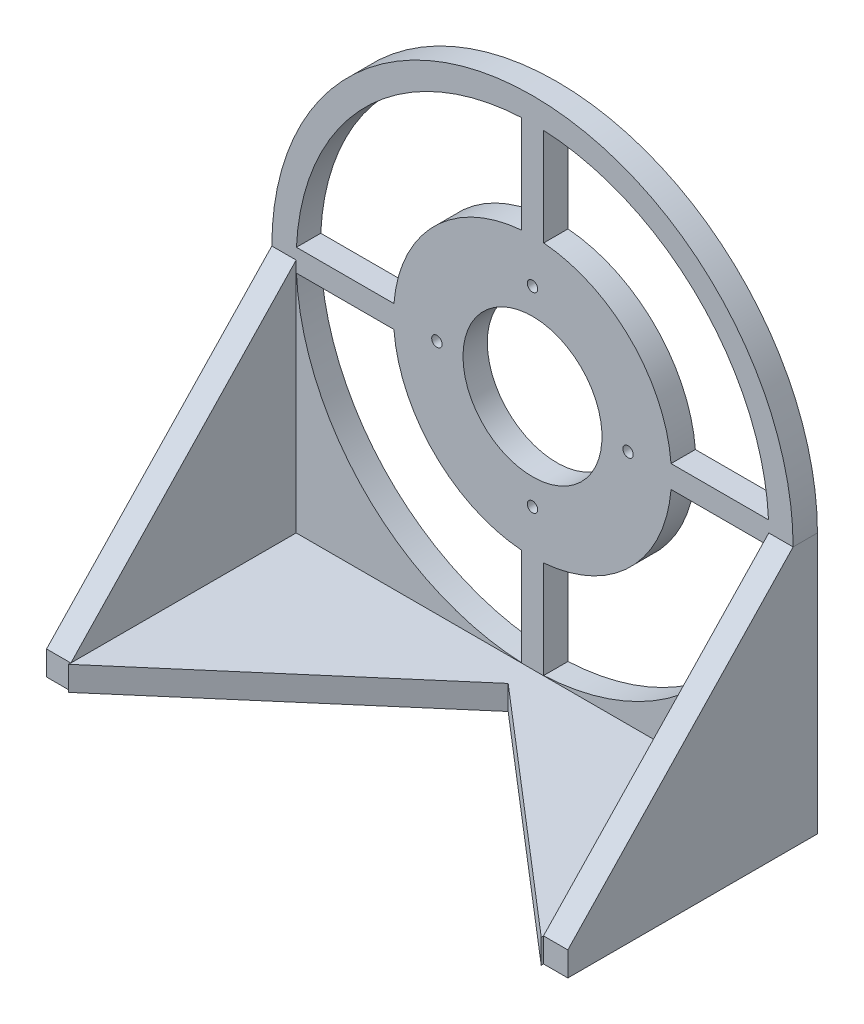
SolidWorks part; units mm, degrees
ref_plane "前视基准面" through (0, 0, 0) normal (0, 0, 1) x (1, 0, 0)
ref_plane "上视基准面" through (0, 0, 0) normal (0, 1, 0) x (1, 0, 0)
ref_plane "右视基准面" through (0, 0, 0) normal (1, 0, 0) x (0, 0, -1)
sketch "草图1" plane through (0, 0, 0) normal (0, 0, 1) x (1, 0, 0)
  line L0 (3.2194, 67.9237) -> (3.2194, 39.8702)
  line L1 (-3.2194, 67.9237) -> (-3.2194, 59)
  line L2 (-67.9237, -3.2194) -> (-59, -3.2194)
  line L3 (-59, -3.2194) -> (-39.8702, -3.2194)
  line L4 (-59.016, 3.2194) -> (-67.9237, 3.2194)
  line L5 (-67.9237, 3.2194) -> (-39.8702, 3.2194)
  line L6 (-3.2194, 59) -> (-3.2194, 39.8702)
  line L7 (67.9237, -3.2194) -> (39.8702, -3.2194)
  line L8 (67.9237, 3.2194) -> (59, 3.2194)
  line L9 (59, 3.2194) -> (39.8702, 3.2194)
  line L10 (-3.2194, -67.9237) -> (-3.2194, -39.8702)
  line L11 (3.2194, -67.9237) -> (3.2194, -59)
  line L12 (3.2194, -59) -> (3.2194, -39.8702)
  circle A0 centre (0, 0) radius 75
  arc A1 (-67.9237, -3.2194) -> (-3.2194, -67.9237) centre (0, 0) ccw
  arc A2 (-39.8702, -3.2194) -> (-3.2194, -39.8702) centre (0, 0) ccw
  arc A3 (-3.2194, 39.8702) -> (-39.8702, 3.2194) centre (0, 0) ccw
  arc A4 (-3.2194, 67.9237) -> (-67.9237, 3.2194) centre (0, 0) ccw
  arc A5 (39.8702, 3.2194) -> (3.2194, 39.8702) centre (0, 0) ccw
  arc A6 (67.9237, 3.2194) -> (3.2194, 67.9237) centre (0, 0) ccw
  arc A7 (3.2194, -39.8702) -> (39.8702, -3.2194) centre (0, 0) ccw
  arc A8 (3.2194, -67.9237) -> (67.9237, -3.2194) centre (0, 0) ccw
  circle A9 centre (0, 0) radius 20
  circle A11 centre (0, 27.5) radius 1.5
  circle A12 centre (27.5, 0) radius 1.5
  circle A13 centre (0, -27.5) radius 1.5
  circle A14 centre (-27.5, 0) radius 1.5
  point P10 (-59, 0)
  point P30 (0, 0)
  point P39 (0, 0)
  dimension "D1" = 150
  dimension "D2" = 136
  dimension "D3" = 80
  dimension "D5" = 40
  dimension "D6" = 4
  dimension "D4" = 4
extrude "凸台-拉伸1" add sketch "草图1" along normal blind 7 contours A0 A14 A13 A12 A11 A9 A8 L11 L12 A7 L7 A6 L8 L9 A5 L0 A4 L1 L6 A3 L5 L4 L3 A2 L10 A1 L2
sketch "草图2" plane through (0, 0, 0) normal (0, 0, 1) x (1, 0, 0)
  circle A0 centre (27.5, 0) radius 2.5
  circle A1 centre (0, -27.5) radius 2.5
  circle A2 centre (-27.5, 0) radius 2.5
  circle A3 centre (0, 27.5) radius 2.5
extrude "切除-拉伸1" cut sketch "草图2" along normal blind 4
ref_plane "基准面1" through (0, -75, 0) normal (0, 1, 0) x (1, 0, 0)
sketch "草图3" plane through (0, -75, 0) normal (0, 1, 0) x (1, 0, 0)
  line L2 (-75, -3.5) -> (-75, 0)
  line L5 (0, 0) -> (0, 7)
  line L7 (-75, 0) -> (75, 0)
  line L8 (0, -14) -> (-75, -78.5)
  line L9 (0, -14) -> (75, -78.5)
  line L23 (-75, 0) -> (75, 0) construction
  line L24 (75, 0) -> (75, -78.5)
  line L25 (-75, -3.5) -> (-75, -78.5)
  point P3 (-75, -3.5)
  point P6 (75, -3.5)
extrude "凸台-拉伸2" add sketch "草图3" along normal blind 7
sketch "草图4" plane through (0, 0, 0) normal (0, 0, 1) x (1, 0, 0)
  line L0 (-75, 0) -> (-75, -75)
  line L1 (-75, -75) -> (75, -75)
  line L2 (75, -75) -> (75, 0)
  line L3 (-75, 0) -> (-68, 0)
  line L4 (68, 0) -> (75, 0)
  circle A0 centre (0, 0) radius 75 construction
  arc A1 (-68, 0) -> (68, 0) centre (0, 0) ccw
extrude "凸台-拉伸3" add sketch "草图4" along normal blind 7
ref_plane "基准面2" through (-75, 0, 0) normal (1, 0, 0) x (0, 0, -1)
sketch "草图5" plane through (-75, 0, 0) normal (1, 0, 0) x (0, 0, -1)
  line L1 (0, 0) -> (-7, 0)
  line L2 (-7, 0) -> (-78.5, -75)
  line L4 (0, 0) -> (0, -75)
  line L5 (0, -75) -> (-78.5, -75)
extrude "凸台-拉伸4" add sketch "草图5" along normal blind 7
mirror "镜向1" about plane through (0, 0, 0) normal (1, 0, 0) of "凸台-拉伸4"
sketch "草图6" plane through (-75, 0, 0) normal (1, 0, 0) x (0, 0, -1)
  line L6 (-78.5, -68) -> (-71.8267, -68)
  line L7 (-71.8267, -68) -> (-71.8267, -75)
  line L8 (-71.8267, -75) -> (-78.5, -75)
  line L9 (-78.5, -75) -> (-78.5, -68)
extrude "切除-拉伸2" cut sketch "草图6" along normal blind 7
mirror "镜向5" about plane through (0, 0, 0) normal (1, 0, 0) of "切除-拉伸2"
